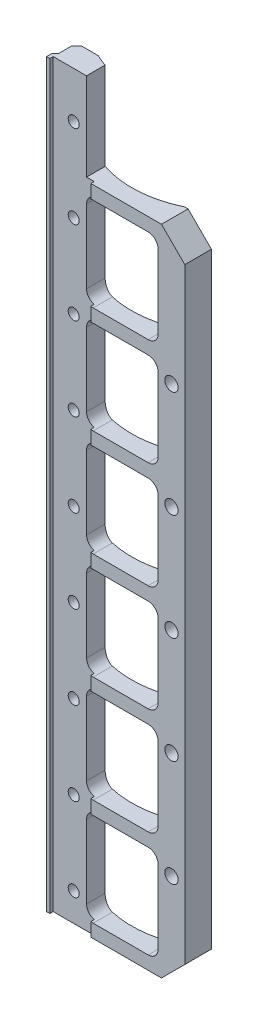
SolidWorks part; units mm, degrees
ref_plane "Plan de face" through (0, 0, 0) normal (0, 0, 1) x (1, 0, 0)
ref_plane "Plan de dessus" through (0, 0, 0) normal (0, 1, 0) x (1, 0, 0)
ref_plane "Plan de droite" through (0, 0, 0) normal (1, 0, 0) x (0, 0, -1)
sketch "Esquisse1" plane through (0, 0, 0) normal (0, 1, 0) x (1, 0, 0)
  line L69 (0, -8) -> (0, 0)
  line L71 (0, 0) -> (-8, 0)
  line L170 (-34, 0) -> (-39, 0)
  line L211 (-39, 0) -> (-40.5, -1.5)
  line L212 (-40.5, -1.5) -> (-40.5, -5.5)
  line L214 (-40.5, -5.5) -> (-41.5, -6.5)
  line L216 (-41.5, -6.5) -> (-41.5, -8)
  line L218 (-41.5, -8) -> (-40.5, -8)
  line L220 (-40.5, -8) -> (-40.5, -7)
  line L222 (-40.5, -7) -> (-28.2, -7)
  line L317 (-28.2, -7) -> (-28.2, -8)
  line L319 (-28.2, -8) -> (0, -8)
  arc A0 (-34, 0) -> (-8, 0) centre (-21, 27.0617) ccw
  point P1 (0, 0)
  point P2 (0, 0)
  point P3 (0, 0)
  point P4 (0, 0)
  point P5 (0, 0)
  point P6 (0, 0)
  point P7 (0, 0)
  dimension "D1" = 12.3
  dimension "D2" = 41.5
extrude "Boss.-Extru.1" add sketch "Esquisse1" along normal blind 222.35
sketch "Esquisse2" plane through (0, 0, 0) normal (0, 0, -1) x (-1, 0, 0)
  line L0 (0, 222.35) -> (0, 0) construction
  line L1 (11, 4) -> (27.5, 4)
  line L2 (8, 7) -> (8, 29)
  line L3 (11, 32) -> (27.5, 32)
  line L4 (30.5, 7) -> (30.5, 29)
  line L5 (40.5, 222.35) -> (40.5, 0) construction
  line L6 (8, 0) -> (34, 0) construction
  arc A0 (27.5, 32) -> (30.5, 29) centre (27.5, 29) cw
  arc A1 (27.5, 4) -> (30.5, 7) centre (27.5, 7) ccw
  arc A2 (11, 4) -> (8, 7) centre (11, 7) cw
  arc A3 (8, 29) -> (11, 32) centre (11, 29) cw
  dimension "D3" = 3
  dimension "D1" = 8
  dimension "D2" = 10
  dimension "D4" = 28
  dimension "D5" = 4
extrude "Enlèv. mat.-Extru.1" cut sketch "Esquisse2" against normal through all
pattern_linear "Répétition linéaire1" count 8 spacing 32 along (0, 1, 0) of "Enlèv. mat.-Extru.1"
sketch "Esquisse3" plane through (0, 0, 7) normal (0, 0, 1) x (1, 0, 0)
  line L0 (-34.35, 0) -> (-34.35, 8.5) construction
  line L1 (-40.5, 0) -> (-28.2, 0) construction
  circle A1 centre (-34.35, 8.5) radius 1.65
  dimension "D1" = 3.3
  dimension "D2" = 8.5
extrude "Enlèv. mat.-Extru.2" cut sketch "Esquisse3" against normal through all
sketch "Esquisse5" plane through (0, 0, 0) normal (0, 0, -1) x (-1, 0, 0)
  line L1 (37.1, 6.9123) -> (37.1, 10.0877)
  line L2 (37.1, 10.0877) -> (34.35, 11.6754)
  line L3 (34.35, 11.6754) -> (31.6, 10.0877)
  line L4 (31.6, 10.0877) -> (31.6, 6.9123)
  line L5 (31.6, 6.9123) -> (34.35, 5.3246)
  line L6 (34.35, 5.3246) -> (37.1, 6.9123)
  circle A0 centre (34.35, 8.5) radius 2.75 construction
  point P1 (38.4735, 10.5987)
  dimension "D1" = 5.5
extrude "Enlèv. mat.-Extru.3" cut sketch "Esquisse5" against normal blind 3
pattern_linear "Répétition linéaire2" count 9 spacing 25 along (0, 1, 0) of "Enlèv. mat.-Extru.3", "Enlèv. mat.-Extru.2"
sketch "Esquisse7" plane through (0, 0, 0) normal (0, 0, -1) x (-1, 0, 0)
  line L0 (4, 0) -> (4, 28) construction
  line L1 (0, 0) -> (8, 0) construction
  circle A0 centre (4, 28) radius 2
  dimension "D1" = 4
  dimension "D2" = 28
extrude "Enlèv. mat.-Extru.4" cut sketch "Esquisse7" against normal through all
pattern_linear "Répétition linéaire3" count 5 spacing 32 along (0, 1, 0) of "Enlèv. mat.-Extru.4"
sketch "Esquisse12" plane through (0, 0, 8) normal (0, 0, 1) x (1, 0, 0)
  line L0 (0, 222.35) -> (0, 0) construction
  line L1 (0, 196) -> (-30.5, 196)
  line L2 (0, 196) -> (0, 222.35)
  line L3 (0, 222.35) -> (-30.5, 222.35)
  line L4 (-30.5, 196) -> (-30.5, 222.35)
  line L5 (-11, 196) -> (-27.5, 196) construction
  line L6 (-8.3209, 222.35) -> (0, 222.35) construction
  line L9 (-30.5, 199) -> (-30.5, 221) construction
  point P8 (-25.2816, 228)
  point P11 (-27.0488, 228)
extrude "Enlèv. mat.-Extru.6" cut sketch "Esquisse12" against normal through all
chamfer "Chanfrein1" distance 7 angle 45 2 edges at (0, 0, 4) (0, 196, 4)
